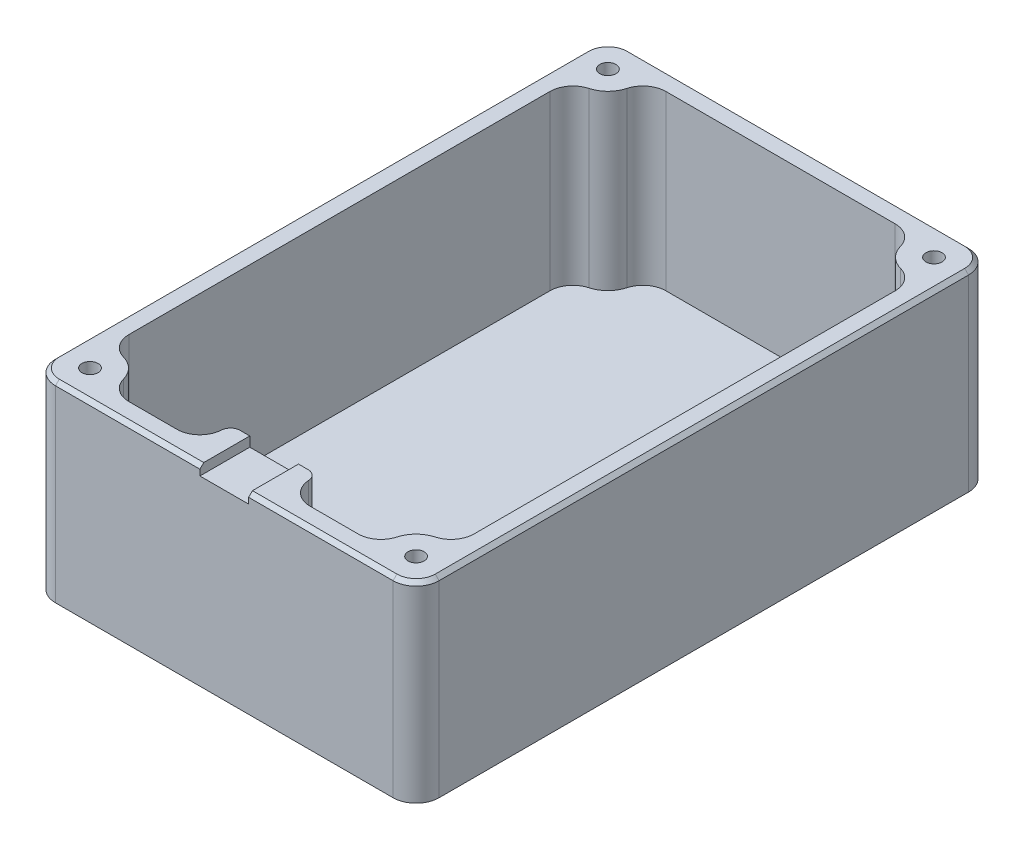
SolidWorks part; units mm, degrees
material "99.5% Aluminum Oxide"
ref_plane "Front Plane" through (0, 0, 0) normal (0, 0, 1) x (1, 0, 0)
ref_plane "Top Plane" through (0, 0, 0) normal (0, 1, 0) x (1, 0, 0)
ref_plane "Right Plane" through (0, 0, 0) normal (1, 0, 0) x (0, 0, -1)
sketch "Sketch1" plane through (0, 0, 0) normal (0, 1, 0) x (1, 0, 0)
  line L1 (-50, -75) -> (50, -75)
  line L2 (-50, -75) -> (-50, 75)
  line L3 (-50, 75) -> (50, 75)
  line L4 (50, -75) -> (50, 75)
  line L5 (-50, -75) -> (50, 75) construction
  line L6 (-50, 75) -> (50, -75) construction
  point P0 (0, 0)
  dimension "D1" = 150
  dimension "D2" = 100
extrude "Boss-Extrude1" add sketch "Sketch1" along normal mid plane 50
sketch "Sketch2" plane through (0, 25, 0) normal (0, 1, 0) x (1, 0, 0)
  line L0 (50, 75) -> (-50, 75) construction
  line L1 (-42.5, -67.5) -> (42.5, -67.5) construction
  line L2 (-42.5, -67.5) -> (-42.5, 67.5) construction
  line L3 (-42.5, 67.5) -> (42.5, 67.5) construction
  line L4 (42.5, -67.5) -> (42.5, 67.5) construction
  line L5 (-42.5, -67.5) -> (42.5, 67.5) construction
  line L6 (-42.5, 67.5) -> (42.5, -67.5) construction
  line L7 (-50, 75) -> (-50, -75) construction
  circle A0 centre (-42.5, 67.5) radius 2.5 construction
  point P0 (0, 0)
  point P7 (-42.5, 70)
  point P8 (-45, 67.5)
  dimension "D1" = 5
  dimension "D2" = 5
  dimension "D3" = 5
hole_wizard "Tap Drill for M5x0.8 Tap1" positions "3DSketch1" profile "Sketch4" hole size "M5x0.8" standard "ANSI Metric"
sketch3d "3DSketch1"
  point P0 (-42.5, 25, -67.5)
  point P3 (42.5, 25, -67.5)
  point P6 (42.5, 25, 67.5)
  point P9 (-42.5, 25, 67.5)
sketch "Sketch4" plane through (-42.5, 25, -67.5) normal (1, 0, 0) x (0, 0, 1)
  line L0 (0, 0) -> (0, 21.2618)
  line L1 (0, 21.2618) -> (2.1, 20)
  line L2 (2.1, 20) -> (2.1, 0)
  line L5 (2.1, 0) -> (0, 0)
  line L10 (0, 21.2618) -> (-2.1, 20) construction
  line L11 (0, -6.35) -> (0, 107.95) construction
  dimension "Hole Dia." = 4.2
  dimension "Hole Depth" = 20
  dimension "Drill Angle" = 118
sketch "Sketch5" plane through (0, 25, 0) normal (0, 1, 0) x (1, 0, 0)
  line L0 (-45, 60.8547) -> (-45, -60.8547)
  line L1 (-50, 75) -> (-50, -75) construction
  line L2 (-35.8547, 70) -> (35.8547, 70)
  line L3 (-11.35, -62) -> (11.35, -62)
  line L4 (50, 75) -> (-50, 75) construction
  line L5 (0, 0) -> (0, 50000) construction
  line L6 (0, 0) -> (50000, 0) construction
  line L7 (45, 60.8547) -> (45, -60.8547)
  line L8 (-35.8547, -70) -> (-11.35, -70)
  line L9 (-50, -75) -> (50, -75) construction
  line L10 (-11.35, -62) -> (-11.35, -70)
  line L11 (11.35, -62) -> (11.35, -70)
  line L12 (11.35, -70) -> (35.8547, -70)
  circle A0 centre (-42.5, 67.5) radius 2.1 construction
  circle A1 centre (-42.5, 67.5) radius 2.1 construction
  arc A2 (-35.8547, 70) -> (-45, 60.8547) centre (-42.5, 67.5) cw
  arc A3 (35.8547, 70) -> (45, 60.8547) centre (42.5, 67.5) ccw
  arc A4 (35.8547, -70) -> (45, -60.8547) centre (42.5, -67.5) cw
  arc A5 (-35.8547, -70) -> (-45, -60.8547) centre (-42.5, -67.5) ccw
  point P17 (0, 70)
  point P21 (45, 0)
  point P26 (-45, 0)
  point P28 (0, -62)
  dimension "D1" = 5
  dimension "D2" = 5
  dimension "D3" = 5
  dimension "D4" = 22.7
  dimension "D5" = 13
extrude "Cut-Extrude1" cut sketch "Sketch5" against normal offset from surface (45 mm away) 5 up to face at (0, -25, 0)
sketch "Sketch6" plane through (0, 25, 0) normal (0, 1, 0) x (1, 0, 0)
  line L0 (0, -62) -> (0, -50062) construction
  line L1 (-11.35, -62) -> (11.35, -62) construction
  line L2 (-50, -75) -> (50, -75) construction
  line L3 (-6.35, -75) -> (6.35, -75)
  line L4 (-6.35, -75) -> (-6.35, -62)
  line L5 (-6.35, -62) -> (6.35, -62)
  line L6 (6.35, -75) -> (6.35, -62)
  line L7 (-6.35, -75) -> (6.35, -62) construction
  line L8 (-6.35, -62) -> (6.35, -75) construction
  point P4 (0, -62)
  point P5 (0, -68.5)
  dimension "D1" = 12.7
extrude "Cut-Extrude2" cut sketch "Sketch6" against normal blind 2.54
fillet "Fillet1" radius 6 14 edges at (50, 0, -75) (-50, 0, -75) (-50, 0, 75) (50, 0, 75) (45, 2.5, -60.8547) (45, 2.5, 60.8547) (35.8547, 2.5, 70) (11.35, 2.5, 70) (-11.35, 2.5, 70) (-35.8547, 2.5, 70) (-45, 2.5, 60.8547) (35.8547, 2.5, -70) (-45, 2.5, -60.8547) (-35.8547, 2.5, -70)
fillet "Fillet3" radius 2.5 2 edges at (11.35, 2.5, 62) (-11.35, 2.5, 62)
chamfer "Chamfer1" distance 1 angle 45 9 edges at (25.175, 25, 75) (48.2426, 25, 73.2426) (50, 25, 0) (48.2426, 25, -73.2426) (0, 25, -75) (-25.175, 25, 75) (-48.2426, 25, -73.2426) (-48.2426, 25, 73.2426) (-50, 25, 0)
